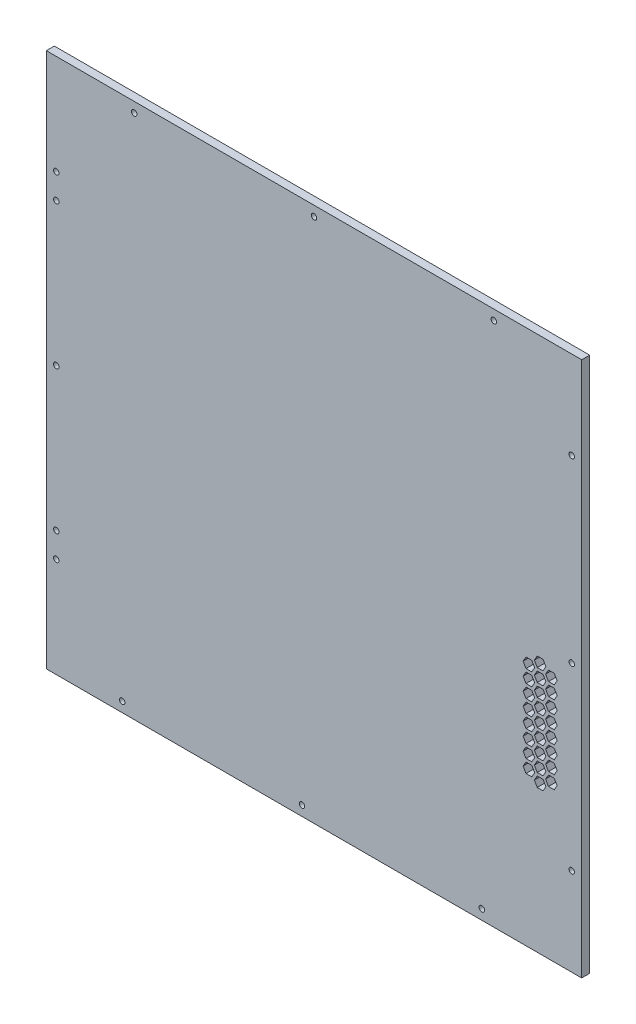
SolidWorks part; units mm, degrees
ref_plane "Front Plane" through (0, 0, 0) normal (0, 0, 1) x (1, 0, 0)
ref_plane "Top Plane" through (0, 0, 0) normal (0, 1, 0) x (1, 0, 0)
ref_plane "Right Plane" through (0, 0, 0) normal (1, 0, 0) x (0, 0, -1)
sketch "Sketch1" plane through (0, 0, 0) normal (0, 0, 1) x (1, 0, 0)
  line L1 (-268, 268) -> (268, 268)
  line L2 (-268, 268) -> (-268, -268)
  line L3 (-268, -268) -> (268, -268)
  line L4 (268, 268) -> (268, -268)
  line L5 (-268, 268) -> (268, -268) construction
  line L6 (-268, -268) -> (268, 268) construction
  line L7 (-258, 258) -> (258, 258) construction
  line L8 (-258, 258) -> (-258, -258) construction
  line L9 (-258, -258) -> (258, -258) construction
  line L10 (258, 258) -> (258, -258) construction
  circle A0 centre (0, 258) radius 2.75
  circle A1 centre (-180, 258) radius 2.75
  circle A2 centre (180, 258) radius 2.75
  circle A3 centre (258, 0.0001) radius 2.75
  circle A4 centre (258, 180.0001) radius 2.75
  circle A5 centre (258, -179.9999) radius 2.75
  circle A6 centre (-12.0095, -258) radius 2.75
  circle A7 centre (167.9905, -258) radius 2.75
  circle A8 centre (-192.0095, -258) radius 2.75
  circle A9 centre (-257.9999, 0.0001) radius 2.75
  circle A10 centre (-257.9999, -167.9905) radius 2.75
  circle A11 centre (-257.9999, 168.0095) radius 2.75
  circle A12 centre (-257.9999, 143.0095) radius 2.75
  circle A13 centre (-257.9999, -142.9905) radius 2.75
  point P0 (0, 0)
  point P16 (0, 258)
  point P41 (-6.0047, 6.0048)
  dimension "D3" = 180
  dimension "D6" = 5.5
  dimension "D1" = 536
  dimension "D2" = 516
  dimension "D4" = 180
  dimension "D7" = 311
  dimension "D5" = 25
  dimension "D8" = 25
extrude "Boss-Extrude1" add sketch "Sketch1" along normal blind 8
sketch "Sketch3" plane through (0, 0, 8) normal (0, 0, 1) x (1, 0, 0)
  line L0 (226.3667, -29.0876) -> (226.3667, -16.0876) construction
  line L1 (243.3985, -22.5876) -> (240.5118, -17.5876)
  line L2 (220.8819, -22.5876) -> (217.9951, -17.5876)
  line L3 (217.9951, -17.5876) -> (212.2216, -17.5876)
  line L4 (212.2216, -17.5876) -> (209.3349, -22.5876)
  line L5 (240.5118, -17.5876) -> (234.7383, -17.5876)
  line L6 (234.7383, -17.5876) -> (231.8515, -22.5876)
  line L7 (231.8515, -22.5876) -> (234.7383, -27.5876)
  line L8 (209.3349, -22.5876) -> (212.2216, -27.5876)
  line L9 (212.2216, -27.5876) -> (217.9951, -27.5876)
  line L10 (217.9951, -27.5876) -> (220.8819, -22.5876)
  line L11 (232.1402, -29.0876) -> (229.2534, -24.0876)
  line L20 (229.2534, -24.0876) -> (223.4799, -24.0876)
  line L21 (223.4799, -24.0876) -> (220.5932, -29.0876)
  line L22 (220.5932, -29.0876) -> (223.4799, -34.0876)
  line L23 (223.4799, -34.0876) -> (229.2534, -34.0876)
  line L24 (229.2534, -34.0876) -> (232.1402, -29.0876)
  line L25 (232.1402, -16.0876) -> (229.2534, -11.0876)
  line L26 (229.2534, -11.0876) -> (223.4799, -11.0876)
  line L27 (223.4799, -11.0876) -> (220.5932, -16.0876)
  line L28 (220.5932, -16.0876) -> (223.4799, -21.0876)
  line L29 (223.4799, -21.0876) -> (229.2534, -21.0876)
  line L30 (229.2534, -21.0876) -> (232.1402, -16.0876)
  line L31 (234.7383, -27.5876) -> (240.5118, -27.5876)
  line L32 (240.5118, -27.5876) -> (243.3985, -22.5876)
  line L33 (226.3667, -16.0876) -> (237.625, -22.5876) construction
  line L34 (237.625, -22.5876) -> (226.3667, -29.0876) construction
  line L35 (226.3667, -29.0876) -> (215.1084, -22.5876) construction
  line L36 (215.1084, -22.5876) -> (226.3667, -16.0876) construction
  line L37 (243.3985, -35.5876) -> (240.5118, -30.5876)
  line L38 (220.8819, -35.5876) -> (217.9951, -30.5876)
  line L39 (217.9951, -30.5876) -> (212.2216, -30.5876)
  line L40 (212.2216, -30.5876) -> (209.3349, -35.5876)
  line L41 (240.5118, -30.5876) -> (234.7383, -30.5876)
  line L42 (234.7383, -30.5876) -> (231.8515, -35.5876)
  line L43 (231.8515, -35.5876) -> (234.7383, -40.5876)
  line L44 (209.3349, -35.5876) -> (212.2216, -40.5876)
  line L45 (212.2216, -40.5876) -> (217.9951, -40.5876)
  line L46 (217.9951, -40.5876) -> (220.8819, -35.5876)
  line L47 (232.1402, -42.0876) -> (229.2534, -37.0876)
  line L48 (229.2534, -37.0876) -> (223.4799, -37.0876)
  line L49 (223.4799, -37.0876) -> (220.5932, -42.0876)
  line L50 (220.5932, -42.0876) -> (223.4799, -47.0876)
  line L51 (223.4799, -47.0876) -> (229.2534, -47.0876)
  line L52 (229.2534, -47.0876) -> (232.1402, -42.0876)
  line L53 (234.7383, -40.5876) -> (240.5118, -40.5876)
  line L54 (240.5118, -40.5876) -> (243.3985, -35.5876)
  line L55 (237.625, -35.5876) -> (226.3667, -42.0876) construction
  line L56 (226.3667, -42.0876) -> (215.1084, -35.5876) construction
  line L57 (243.3985, -48.5876) -> (240.5118, -43.5876)
  line L58 (220.8819, -48.5876) -> (217.9951, -43.5876)
  line L59 (217.9951, -43.5876) -> (212.2216, -43.5876)
  line L60 (212.2216, -43.5876) -> (209.3349, -48.5876)
  line L61 (240.5118, -43.5876) -> (234.7383, -43.5876)
  line L62 (234.7383, -43.5876) -> (231.8515, -48.5876)
  line L63 (231.8515, -48.5876) -> (234.7383, -53.5876)
  line L64 (209.3349, -48.5876) -> (212.2216, -53.5876)
  line L65 (212.2216, -53.5876) -> (217.9951, -53.5876)
  line L66 (217.9951, -53.5876) -> (220.8819, -48.5876)
  line L67 (232.1402, -55.0876) -> (229.2534, -50.0876)
  line L68 (229.2534, -50.0876) -> (223.4799, -50.0876)
  line L69 (223.4799, -50.0876) -> (220.5932, -55.0876)
  line L70 (220.5932, -55.0876) -> (223.4799, -60.0876)
  line L71 (223.4799, -60.0876) -> (229.2534, -60.0876)
  line L72 (229.2534, -60.0876) -> (232.1402, -55.0876)
  line L73 (234.7383, -53.5876) -> (240.5118, -53.5876)
  line L74 (240.5118, -53.5876) -> (243.3985, -48.5876)
  line L75 (237.625, -48.5876) -> (226.3667, -55.0876) construction
  line L76 (226.3667, -55.0876) -> (215.1084, -48.5876) construction
  line L77 (243.3985, -61.5876) -> (240.5118, -56.5876)
  line L78 (220.8819, -61.5876) -> (217.9951, -56.5876)
  line L79 (217.9951, -56.5876) -> (212.2216, -56.5876)
  line L80 (212.2216, -56.5876) -> (209.3349, -61.5876)
  line L81 (240.5118, -56.5876) -> (234.7383, -56.5876)
  line L82 (234.7383, -56.5876) -> (231.8515, -61.5876)
  line L83 (231.8515, -61.5876) -> (234.7383, -66.5876)
  line L84 (209.3349, -61.5876) -> (212.2216, -66.5876)
  line L85 (212.2216, -66.5876) -> (217.9951, -66.5876)
  line L86 (217.9951, -66.5876) -> (220.8819, -61.5876)
  line L87 (232.1402, -68.0876) -> (229.2534, -63.0876)
  line L88 (229.2534, -63.0876) -> (223.4799, -63.0876)
  line L89 (223.4799, -63.0876) -> (220.5932, -68.0876)
  line L90 (220.5932, -68.0876) -> (223.4799, -73.0876)
  line L91 (223.4799, -73.0876) -> (229.2534, -73.0876)
  line L92 (229.2534, -73.0876) -> (232.1402, -68.0876)
  line L93 (234.7383, -66.5876) -> (240.5118, -66.5876)
  line L94 (240.5118, -66.5876) -> (243.3985, -61.5876)
  line L95 (237.625, -61.5876) -> (226.3667, -68.0876) construction
  line L96 (226.3667, -68.0876) -> (215.1084, -61.5876) construction
  line L97 (243.3985, -74.5876) -> (240.5118, -69.5876)
  line L98 (220.8819, -74.5876) -> (217.9951, -69.5876)
  line L99 (217.9951, -69.5876) -> (212.2216, -69.5876)
  line L100 (212.2216, -69.5876) -> (209.3349, -74.5876)
  line L101 (240.5118, -69.5876) -> (234.7383, -69.5876)
  line L102 (234.7383, -69.5876) -> (231.8515, -74.5876)
  line L103 (231.8515, -74.5876) -> (234.7383, -79.5876)
  line L104 (209.3349, -74.5876) -> (212.2216, -79.5876)
  line L105 (212.2216, -79.5876) -> (217.9951, -79.5876)
  line L106 (217.9951, -79.5876) -> (220.8819, -74.5876)
  line L107 (232.1402, -81.0876) -> (229.2534, -76.0876)
  line L108 (229.2534, -76.0876) -> (223.4799, -76.0876)
  line L109 (223.4799, -76.0876) -> (220.5932, -81.0876)
  line L110 (220.5932, -81.0876) -> (223.4799, -86.0876)
  line L111 (223.4799, -86.0876) -> (229.2534, -86.0876)
  line L112 (229.2534, -86.0876) -> (232.1402, -81.0876)
  line L113 (234.7383, -79.5876) -> (240.5118, -79.5876)
  line L114 (240.5118, -79.5876) -> (243.3985, -74.5876)
  line L115 (237.625, -74.5876) -> (226.3667, -81.0876) construction
  line L116 (226.3667, -81.0876) -> (215.1084, -74.5876) construction
  line L117 (243.3985, -87.5876) -> (240.5118, -82.5876)
  line L118 (220.8819, -87.5876) -> (217.9951, -82.5876)
  line L119 (217.9951, -82.5876) -> (212.2216, -82.5876)
  line L120 (212.2216, -82.5876) -> (209.3349, -87.5876)
  line L121 (240.5118, -82.5876) -> (234.7383, -82.5876)
  line L122 (234.7383, -82.5876) -> (231.8515, -87.5876)
  line L123 (231.8515, -87.5876) -> (234.7383, -92.5876)
  line L124 (209.3349, -87.5876) -> (212.2216, -92.5876)
  line L125 (212.2216, -92.5876) -> (217.9951, -92.5876)
  line L126 (217.9951, -92.5876) -> (220.8819, -87.5876)
  line L127 (232.1402, -94.0876) -> (229.2534, -89.0876)
  line L128 (229.2534, -89.0876) -> (223.4799, -89.0876)
  line L129 (223.4799, -89.0876) -> (220.5932, -94.0876)
  line L130 (220.5932, -94.0876) -> (223.4799, -99.0876)
  line L131 (223.4799, -99.0876) -> (229.2534, -99.0876)
  line L132 (229.2534, -99.0876) -> (232.1402, -94.0876)
  line L133 (234.7383, -92.5876) -> (240.5118, -92.5876)
  line L134 (240.5118, -92.5876) -> (243.3985, -87.5876)
  line L135 (237.625, -87.5876) -> (226.3667, -94.0876) construction
  line L136 (226.3667, -94.0876) -> (215.1084, -87.5876) construction
  line L137 (243.3985, -100.5876) -> (240.5118, -95.5876)
  line L138 (220.8819, -100.5876) -> (217.9951, -95.5876)
  line L139 (217.9951, -95.5876) -> (212.2216, -95.5876)
  line L140 (212.2216, -95.5876) -> (209.3349, -100.5876)
  line L141 (240.5118, -95.5876) -> (234.7383, -95.5876)
  line L142 (234.7383, -95.5876) -> (231.8515, -100.5876)
  line L143 (231.8515, -100.5876) -> (234.7383, -105.5876)
  line L144 (209.3349, -100.5876) -> (212.2216, -105.5876)
  line L145 (212.2216, -105.5876) -> (217.9951, -105.5876)
  line L146 (217.9951, -105.5876) -> (220.8819, -100.5876)
  line L147 (232.1402, -107.0876) -> (229.2534, -102.0876)
  line L148 (229.2534, -102.0876) -> (223.4799, -102.0876)
  line L149 (223.4799, -102.0876) -> (220.5932, -107.0876)
  line L150 (220.5932, -107.0876) -> (223.4799, -112.0876)
  line L151 (223.4799, -112.0876) -> (229.2534, -112.0876)
  line L152 (229.2534, -112.0876) -> (232.1402, -107.0876)
  line L153 (234.7383, -105.5876) -> (240.5118, -105.5876)
  line L154 (240.5118, -105.5876) -> (243.3985, -100.5876)
  line L155 (237.625, -100.5876) -> (226.3667, -107.0876) construction
  line L156 (226.3667, -107.0876) -> (215.1084, -100.5876) construction
  line L157 (243.3985, -113.5876) -> (240.5118, -108.5876)
  line L158 (220.8819, -113.5876) -> (217.9951, -108.5876)
  line L159 (217.9951, -108.5876) -> (212.2216, -108.5876)
  line L160 (212.2216, -108.5876) -> (209.3349, -113.5876)
  line L161 (240.5118, -108.5876) -> (234.7383, -108.5876)
  line L162 (234.7383, -108.5876) -> (231.8515, -113.5876)
  line L163 (231.8515, -113.5876) -> (234.7383, -118.5876)
  line L164 (209.3349, -113.5876) -> (212.2216, -118.5876)
  line L165 (212.2216, -118.5876) -> (217.9951, -118.5876)
  line L166 (217.9951, -118.5876) -> (220.8819, -113.5876)
  line L167 (232.1402, -120.0876) -> (229.2534, -115.0876)
  line L168 (229.2534, -115.0876) -> (223.4799, -115.0876)
  line L169 (223.4799, -115.0876) -> (220.5932, -120.0876)
  line L170 (220.5932, -120.0876) -> (223.4799, -125.0876)
  line L171 (223.4799, -125.0876) -> (229.2534, -125.0876)
  line L172 (229.2534, -125.0876) -> (232.1402, -120.0876)
  line L173 (234.7383, -118.5876) -> (240.5118, -118.5876)
  line L174 (240.5118, -118.5876) -> (243.3985, -113.5876)
  line L175 (237.625, -113.5876) -> (226.3667, -120.0876) construction
  line L176 (226.3667, -120.0876) -> (215.1084, -113.5876) construction
  circle A0 centre (215.1084, -22.5876) radius 5 construction
  circle A1 centre (226.3667, -29.0876) radius 5 construction
  circle A2 centre (226.3667, -16.0876) radius 5 construction
  circle A3 centre (237.625, -22.5876) radius 5 construction
  circle A4 centre (215.1084, -35.5876) radius 5 construction
  circle A5 centre (226.3667, -42.0876) radius 5 construction
  circle A6 centre (237.625, -35.5876) radius 5 construction
  circle A7 centre (215.1084, -48.5876) radius 5 construction
  circle A8 centre (226.3667, -55.0876) radius 5 construction
  circle A9 centre (237.625, -48.5876) radius 5 construction
  circle A10 centre (215.1084, -61.5876) radius 5 construction
  circle A11 centre (226.3667, -68.0876) radius 5 construction
  circle A12 centre (237.625, -61.5876) radius 5 construction
  circle A13 centre (215.1084, -74.5876) radius 5 construction
  circle A14 centre (226.3667, -81.0876) radius 5 construction
  circle A15 centre (237.625, -74.5876) radius 5 construction
  circle A16 centre (215.1084, -87.5876) radius 5 construction
  circle A17 centre (226.3667, -94.0876) radius 5 construction
  circle A18 centre (237.625, -87.5876) radius 5 construction
  circle A19 centre (215.1084, -100.5876) radius 5 construction
  circle A20 centre (226.3667, -107.0876) radius 5 construction
  circle A21 centre (237.625, -100.5876) radius 5 construction
  circle A22 centre (215.1084, -113.5876) radius 5 construction
  circle A23 centre (226.3667, -120.0876) radius 5 construction
  circle A24 centre (237.625, -113.5876) radius 5 construction
  dimension "D1" = 3
  dimension "D3" = 3
  dimension "D4" = 8
extrude "Cut-Extrude4" cut sketch "Sketch3" against normal blind 10
